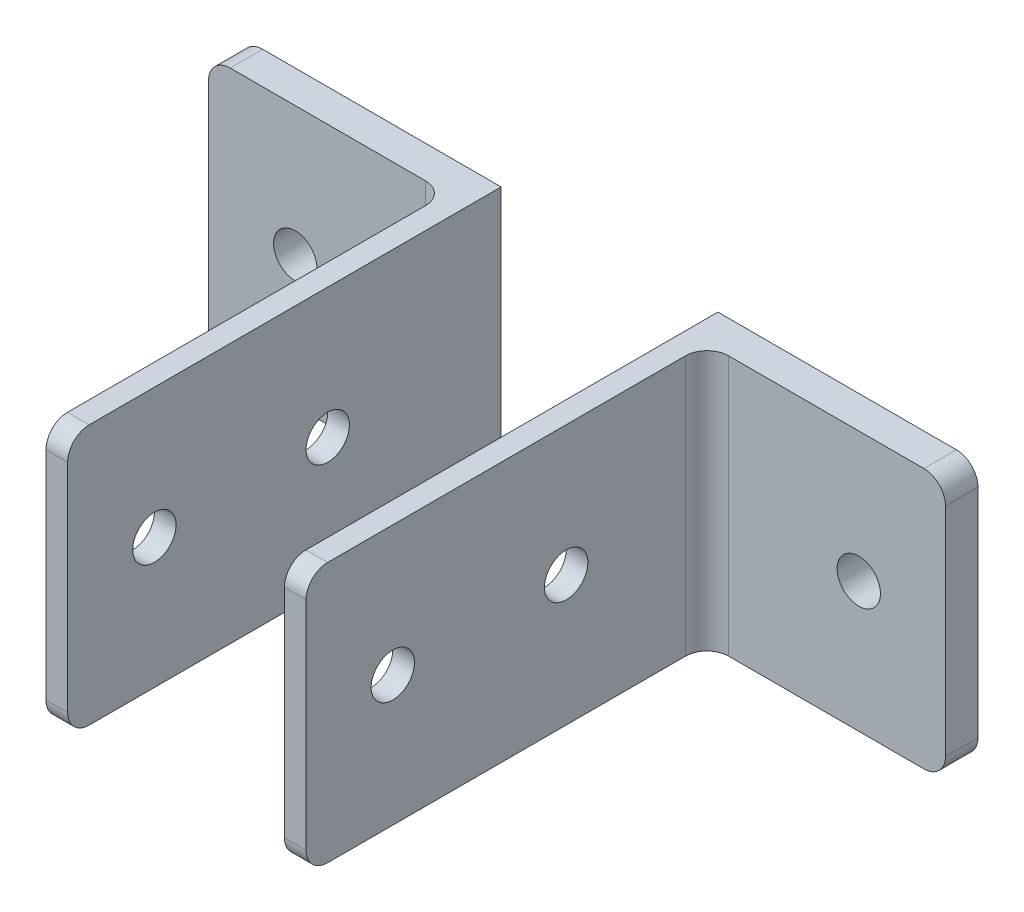
SolidWorks part; units mm, degrees
ref_plane "Front" through (0, 0, 0) normal (0, 0, 1) x (1, 0, 0)
ref_plane "Top" through (0, 0, 0) normal (0, 1, 0) x (1, 0, 0)
ref_plane "Right" through (0, 0, 0) normal (1, 0, 0) x (0, 0, -1)
sketch "Sketch1" plane through (0, 0, 0) normal (0, 1, 0) x (1, 0, 0)
  line L0 (-53.975, 0) -> (-15.875, 0)
  line L1 (53.975, 0) -> (53.975, -4.7625)
  line L2 (53.975, -4.7625) -> (19.05, -4.7625)
  line L3 (19.05, -4.7625) -> (19.05, -63.5)
  line L4 (19.05, -63.5) -> (15.875, -63.5)
  line L5 (15.875, -63.5) -> (15.875, 0)
  line L6 (15.875, 0) -> (53.975, 0)
  line L7 (-15.875, 0) -> (-15.875, -63.5)
  line L8 (-15.875, -63.5) -> (-19.05, -63.5)
  line L9 (-19.05, -63.5) -> (-19.05, -4.7625)
  line L10 (-19.05, -4.7625) -> (-53.975, -4.7625)
  line L11 (-53.975, -4.7625) -> (-53.975, 0)
  line L12 (-15.875, 0) -> (15.875, 0) construction
  dimension "D2" = 31.75
  dimension "Wall Thickness 2" = 4.7625
  dimension "C" = 38.1
  dimension "A" = 63.5
  dimension "Wall Thickness 1" = 3.175
extrude "Boss-Extrude2" add sketch "Sketch1" along normal mid plane 38.1
sketch "Sketch2" plane through (0, 0, 0) normal (0, 0, 1) x (1, 0, 0)
  line L0 (-41.275, 0) -> (41.275, 0) construction
  line L1 (15.875, 19.05) -> (15.875, -19.05) construction
  circle A0 centre (-41.275, 0) radius 3.175
  circle A1 centre (41.275, 0) radius 3.175
  dimension "Hole Dia" = 6.35
  dimension "Hole Spacing 1" = 25.4
extrude "Extrude2" cut sketch "Sketch2" along normal through all
sketch "Sketch3" plane through (0, 0, -0.6698) normal (1, 0, 0) x (0, 0, -1)
  line L0 (-64.1698, 19.05) -> (-64.1698, -19.05) construction
  line L1 (-51.4698, 0) -> (-26.0698, 0) construction
  circle A0 centre (-51.4698, 0) radius 3.175
  circle A1 centre (-26.0698, 0) radius 3.175
  dimension "D1" = 6.35
  dimension "Hole Spacing 2" = 12.7
  dimension "Hole Spacing 3" = 25.4
extrude "Extrude3" cut sketch "Sketch3" along normal through all and the other way through all
fillet "Fillet3" radius 3.1623 5 edges at (17.4625, -19.05, 63.5) (17.4625, 19.05, 63.5) (19.05, 0, 4.7625) (53.975, -19.05, 2.3813) (53.975, 19.05, 2.3813)
fillet "Fillet4" radius 3.1623 5 edges at (-53.975, -19.05, 2.3813) (-53.975, 19.05, 2.3813) (-19.05, 0, 4.7625) (-17.4625, -19.05, 63.5) (-17.4625, 19.05, 63.5)
sketch "Sketch4" plane through (0, 0, 0) normal (0, 1, 0) x (1, 0, 0)
  line L0 (19.05, -22.225) -> (15.875, -22.225) construction
  line L1 (-15.875, -22.225) -> (-19.05, -22.225) construction
  line L2 (-15.875, -47.625) -> (-19.05, -47.625) construction
  line L3 (-19.05, -53.975) -> (-15.875, -53.975) construction
  line L4 (19.05, -47.625) -> (15.875, -47.625)
  line L5 (15.875, -53.975) -> (19.05, -53.975)
  line L6 (-15.875, -47.625) -> (-19.05, -47.625)
  line L7 (-19.05, -53.975) -> (-15.875, -53.975)
  line L8 (-20.066, -50.8) -> (-14.859, -50.8) construction
  line L9 (-15.875, -50.8) -> (-19.05, -50.8) construction
  line L10 (14.859, -50.8) -> (20.066, -50.8) construction
  line L11 (19.05, -47.625) -> (15.875, -47.625) construction
  line L12 (15.875, -28.575) -> (19.05, -28.575) construction
  line L13 (15.875, -53.975) -> (19.05, -53.975) construction
  line L14 (-19.05, -28.575) -> (-15.875, -28.575) construction
  line L15 (19.05, -53.975) -> (19.05, -47.625) construction
  line L16 (15.875, -47.625) -> (15.875, -53.975) construction
  line L17 (19.05, -22.225) -> (15.875, -22.225)
  line L18 (-15.875, -22.225) -> (-19.05, -22.225)
  line L19 (15.875, -28.575) -> (19.05, -28.575)
  line L20 (-19.05, -28.575) -> (-15.875, -28.575)
  line L21 (14.859, -25.4) -> (20.066, -25.4) construction
  line L22 (-20.066, -25.4) -> (-14.859, -25.4) construction
  line L23 (19.05, -25.4) -> (15.875, -25.4) construction
  point P14 (-17.4625, -50.8)
  point P15 (-17.4625, -47.625)
  point P16 (17.4625, -50.8)
  point P17 (17.4625, -47.625)
  dimension "D1" = 1.016
equation "\"D1@Sketch3\" = \"Hole Dia@Sketch2\""
equation "\"D1@Fillet3\" = \"B@Boss-Extrude2\" * .083"
equation "\"D1@Fillet4\" = \"D1@Fillet3\""
